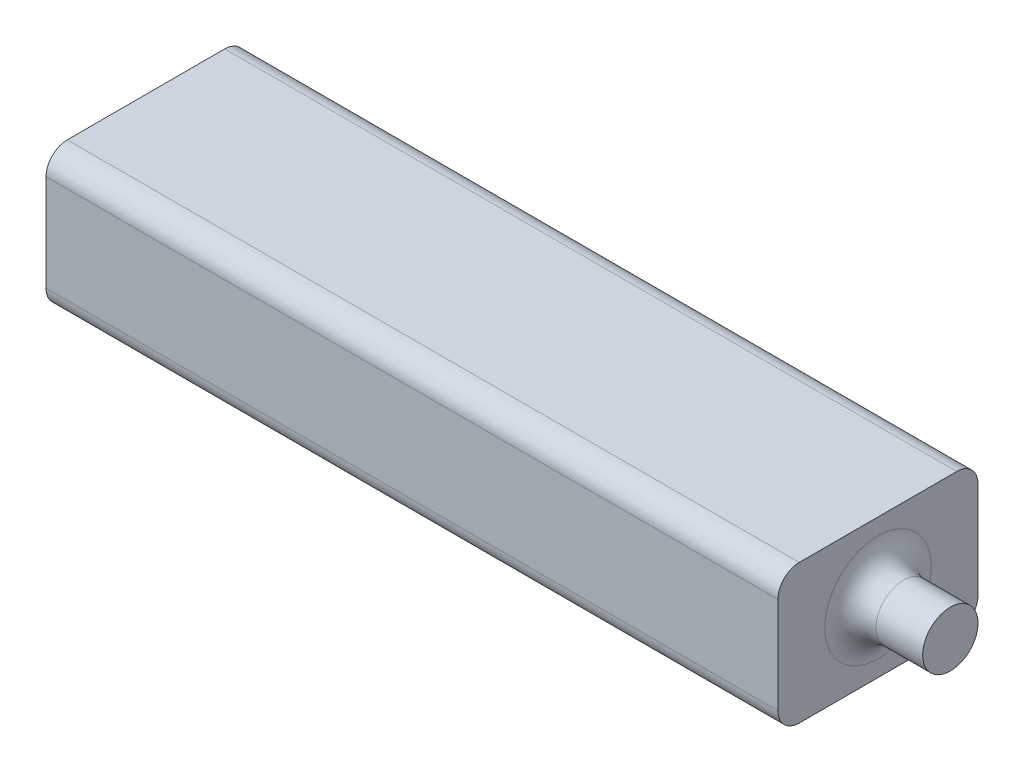
SolidWorks part; units mm, degrees
ref_plane "Front Plane" through (0, 0, 0) normal (0, 0, 1) x (1, 0, 0)
ref_plane "Top Plane" through (0, 0, 0) normal (0, 1, 0) x (1, 0, 0)
ref_plane "Right Plane" through (0, 0, 0) normal (1, 0, 0) x (0, 0, -1)
sketch "Sketch1" plane through (0, 0, 0) normal (1, 0, 0) x (0, 0, -1)
  line L1 (-9.25, -8.175) -> (9.25, -8.175)
  line L2 (-11.75, -5.675) -> (-11.75, 5.675)
  line L3 (-9.25, 8.175) -> (9.25, 8.175)
  line L4 (11.75, -5.675) -> (11.75, 5.675)
  line L5 (-11.75, -8.175) -> (11.75, 8.175) construction
  line L6 (-11.75, 8.175) -> (11.75, -8.175) construction
  arc A0 (-9.25, -8.175) -> (-11.75, -5.675) centre (-9.25, -5.675) cw
  arc A1 (9.25, -8.175) -> (11.75, -5.675) centre (9.25, -5.675) ccw
  arc A2 (9.25, 8.175) -> (11.75, 5.675) centre (9.25, 5.675) cw
  arc A3 (-11.75, 5.675) -> (-9.25, 8.175) centre (-9.25, 5.675) cw
  point P0 (0, 0)
  dimension "D1" = 2.5
  dimension "D2" = 16.35
  dimension "D3" = 23.5
extrude "Boss-Extrude1" add sketch "Sketch1" along normal mid plane 86
sketch "Sketch2" plane through (43, 0, 0) normal (1, 0, 0) x (0, 0, -1)
  circle A0 centre (0, 0) radius 3.25
  dimension "D1" = 6.5
extrude "Boss-Extrude2" add sketch "Sketch2" along normal blind 8.5
fillet "Fillet1" radius 3 1 edges at (43, 0, 3.25)
sketch "Sketch3" plane through (0, 0, -11.75) normal (0, 0, -1) x (-1, 0, 0)
  line L0 (43, -5.675) -> (43, 5.675) construction
  line L1 (-0.5, 0.675) -> (11.5, 0.675)
  line L2 (-0.5, 0.675) -> (-0.5, -3.925)
  line L3 (-0.5, -3.925) -> (11.5, -3.925)
  line L4 (11.5, 0.675) -> (11.5, -3.925)
  line L5 (-43, 8.175) -> (43, 8.175) construction
  line L7 (-6, 0.675) -> (-18, 0.675)
  line L8 (-6, 0.675) -> (-6, -3.925)
  line L9 (-6, -3.925) -> (-18, -3.925)
  line L10 (-18, 0.675) -> (-18, -3.925)
  line L11 (-23.5, 0.675) -> (-35.5, 0.675)
  line L12 (-23.5, 0.675) -> (-23.5, -3.925)
  line L13 (-23.5, -3.925) -> (-35.5, -3.925)
  line L14 (-35.5, 0.675) -> (-35.5, -3.925)
  point P4 (5.5, 0.675)
  dimension "D1" = 37.5
  dimension "D2" = 12
  dimension "D3" = 4.6
  dimension "D4" = 7.5
  dimension "D5" = 5.5
  dimension "D6" = 5.5
extrude "Cut-Extrude1" cut sketch "Sketch3" against normal blind 5
